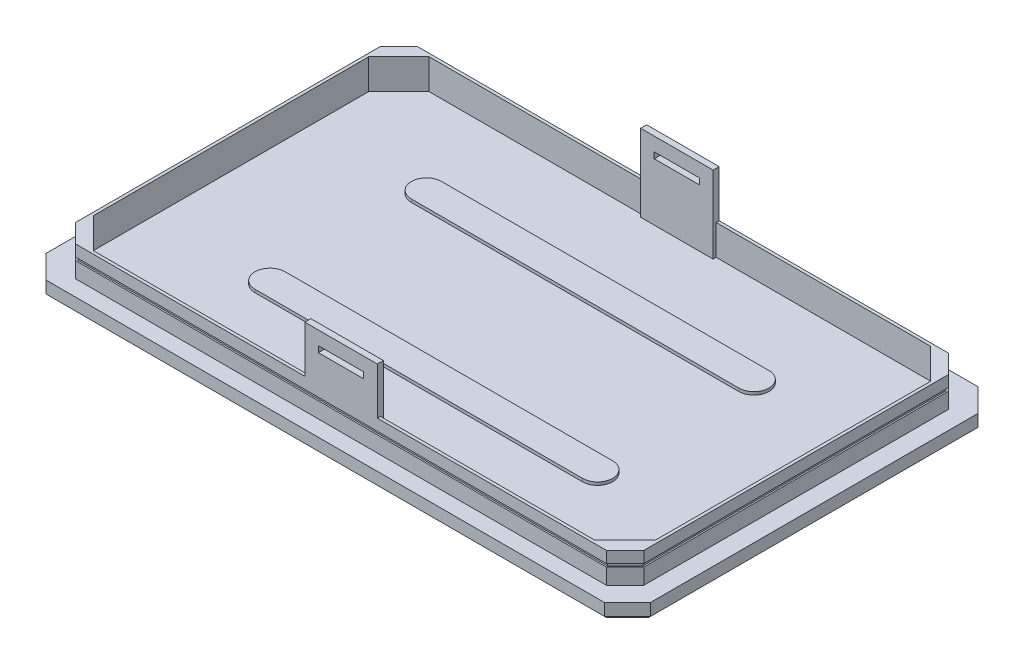
SolidWorks part; units mm, degrees
ref_plane "前视基准面" through (0, 0, 0) normal (0, 0, 1) x (1, 0, 0)
ref_plane "上视基准面" through (0, 0, 0) normal (0, 1, 0) x (1, 0, 0)
ref_plane "右视基准面" through (0, 0, 0) normal (1, 0, 0) x (0, 0, -1)
other "Configuration Table"
sketch "草图1" plane through (0, 0, 0) normal (0, 1, 0) x (1, 0, 0)
  line L0 (-100, 54.16) -> (-92.36, 61.8)
  line L1 (-92.36, -61.8) -> (92.36, -61.8)
  line L2 (-100, -54.16) -> (-100, 54.16)
  line L3 (-92.36, 61.8) -> (92.36, 61.8)
  line L4 (100, -54.16) -> (100, 54.16)
  line L5 (-100, -61.8) -> (100, 61.8) construction
  line L6 (-100, 61.8) -> (100, -61.8) construction
  line L7 (92.36, 61.8) -> (100, 54.16)
  line L8 (92.36, -61.8) -> (100, -54.16)
  line L9 (-100, -54.16) -> (-92.36, -61.8)
  point P0 (0, 0)
  dimension "D1" = 200
  dimension "D2" = 123.6
extrude "凸台-拉伸1" add sketch "草图1" along normal blind 5
sketch "草图2" plane through (0, 5, 0) normal (0, 1, 0) x (1, 0, 0)
  line L0 (-93.97, 50.37) -> (-87.79, 56.55)
  line L1 (-87.79, -56.55) -> (87.79, -56.55)
  line L2 (-93.97, -50.37) -> (-93.97, 50.37)
  line L3 (-87.79, 56.55) -> (87.79, 56.55)
  line L4 (93.97, -50.37) -> (93.97, 50.37)
  line L5 (-93.97, -56.55) -> (93.97, 56.55) construction
  line L6 (-93.97, 56.55) -> (93.97, -56.55) construction
  line L7 (-93.97, -50.37) -> (-87.79, -56.55)
  line L8 (87.79, -56.55) -> (93.97, -50.37)
  line L9 (87.79, 56.55) -> (93.97, 50.37)
  line L10 (-92.97, -45.55) -> (-82.97, -55.55)
  line L11 (-82.97, -55.55) -> (82.97, -55.55)
  line L12 (-92.97, -45.55) -> (-92.97, 45.55)
  line L13 (-82.97, 55.55) -> (82.97, 55.55)
  line L14 (92.97, -45.55) -> (92.97, 45.55)
  line L15 (-92.97, -55.55) -> (92.97, 55.55) construction
  line L16 (-92.97, 55.55) -> (92.97, -55.55) construction
  line L17 (-92.97, 45.55) -> (-82.97, 55.55)
  line L18 (92.97, 45.55) -> (82.97, 55.55)
  line L19 (82.97, -55.55) -> (92.97, -45.55)
  point P0 (0, 0)
  point P14 (0, 0)
  dimension "D1" = 113.1
  dimension "D2" = 187.94
  dimension "D3" = 1
  dimension "D4" = 1
extrude "凸台-拉伸2" add sketch "草图2" along normal blind 10
sketch "支撑架（待调整）" plane through (0, 0, 56.55) normal (0, 0, 1) x (1, 0, 0)
  line L6 (-68.0971, 44.5962) -> (-63.0971, 49.5962)
  line L7 (-49.2657, 49.5962) -> (-44.2657, 44.5962)
  line L9 (-68.0971, 25.3818) -> (-68.0971, 44.5962)
  line L10 (-63.0971, 49.5962) -> (-49.2657, 49.5962)
  line L11 (-44.2657, 22.3818) -> (-44.2657, 44.5962)
  line L12 (-44.2657, 22.3818) -> (-37.8806, 22.3818)
  line L13 (-74.4822, 22.3818) -> (-71.0971, 22.3818)
  line L17 (-80.8673, 15) -> (-74.4822, 22.3818)
  line L18 (-31.4955, 15) -> (-26.4471, 15)
  line L19 (-85.9157, 4.2346) -> (-26.4471, 4.2346)
  line L20 (-85.9157, 4.2346) -> (-85.9157, 15)
  line L21 (-85.9157, 15) -> (-80.8673, 15)
  line L22 (-26.4471, 4.2346) -> (-26.4471, 15)
  line L23 (-37.8806, 22.3818) -> (-31.4955, 15)
  line L24 (-71.0971, 22.3818) -> (-68.0971, 25.3818)
  line L25 (68.0971, 22.3818) -> (68.0971, 44.5962)
  line L27 (26.4471, 4.4781) -> (26.4471, 15)
  line L28 (44.2657, 25.3818) -> (44.2657, 44.5962)
  line L29 (31.4955, 15) -> (37.8806, 22.3818)
  line L30 (80.8673, 15) -> (85.9157, 15)
  line L31 (68.0971, 22.3818) -> (74.4822, 22.3818)
  line L32 (63.0971, 49.5962) -> (68.0971, 44.5962)
  line L33 (26.4471, 4.4781) -> (85.9157, 4.4781)
  line L34 (26.4471, 15) -> (31.4955, 15)
  line L35 (74.4822, 22.3818) -> (80.8673, 15)
  line L36 (49.2657, 49.5962) -> (63.0971, 49.5962)
  line L37 (37.8806, 22.3818) -> (41.2657, 22.3818)
  line L38 (44.2657, 44.5962) -> (49.2657, 49.5962)
  line L39 (85.9157, 4.4781) -> (85.9157, 15)
  line L40 (41.2657, 22.3818) -> (44.2657, 25.3818)
  point P0 (0, 15)
  point P9 (-56.1814, 15)
  point P10 (-56.1814, 15)
  point P11 (-44.2657, 49.5962)
  point P13 (-68.0971, 49.5962)
  point P15 (-68.0971, 22.3818)
  point P17 (-56.1814, 11.4723)
  point P27 (56.1814, 15)
  point P29 (56.1814, 15)
  point P30 (56.1814, 15)
  point P31 (68.0971, 49.5962)
  point P33 (44.2657, 49.5962)
  point P35 (44.2657, 22.3818)
  point P37 (56.1814, 11.4723)
sketch "草图6" plane through (72.17, 0, 72.17) normal (0.7071, 0, 0.7071) x (0.7071, 0, -0.7071)
  line L1 (21.4393, 10.6117) -> (31.2612, 10.6117)
  line L2 (21.4393, 10.6117) -> (21.4393, 10.2265)
  line L3 (21.4393, 10.2265) -> (31.2612, 10.2265)
  line L4 (31.2612, 10.6117) -> (31.2612, 10.2265)
  line L5 (21.4393, 10.6117) -> (31.2612, 10.2265) construction
  line L6 (21.4393, 10.2265) -> (31.2612, 10.6117) construction
  point P0 (26.3502, 10.4191)
extrude "切除-拉伸2" cut sketch "草图6" against normal blind 0.2
sketch "草图7" plane through (0, 5, 0) normal (0, 1, 0) x (1, 0, 0)
  line L5 (87.79, 56.55) -> (-87.79, 56.55) construction
  line L6 (-12, -56.55) -> (12, -56.55)
  line L12 (-12, -56.55) -> (-12, 56.55)
  line L13 (-12, 56.55) -> (12, 56.55)
  line L19 (12, -56.55) -> (12, 56.55)
  line L20 (-12, -56.55) -> (12, 56.55) construction
  line L22 (-12, 56.55) -> (12, -56.55) construction
  line L23 (93.97, -50.37) -> (93.97, 50.37) construction
  line L24 (-93.97, -12) -> (93.97, -12)
  line L25 (-93.97, -12) -> (-93.97, 12)
  line L26 (-93.97, 12) -> (93.97, 12)
  line L27 (93.97, -12) -> (93.97, 12)
  line L28 (-93.97, -12) -> (93.97, 12) construction
  line L29 (-93.97, 12) -> (93.97, -12) construction
  line L31 (-91.97, -54.55) -> (91.97, -54.55)
  line L32 (-91.97, -54.55) -> (-91.97, 54.55)
  line L33 (-91.97, 54.55) -> (91.97, 54.55)
  line L34 (91.97, -54.55) -> (91.97, 54.55)
  line L35 (-91.97, -54.55) -> (91.97, 54.55) construction
  line L36 (-91.97, 54.55) -> (91.97, -54.55) construction
  point P0 (0, 0)
  point P8 (0, 0)
  point P15 (0, 0)
  line M14 (-82.97, -55.55) -> (82.97, -55.55)
  line M18 (82.97, 55.55) -> (-82.97, 55.55)
  dimension "D1" = 24
  dimension "D2" = 24
  dimension "D3" = 2
  dimension "D4" = 2
extrude "凸台-拉伸6" add sketch "草图7" along normal blind 25.5 contours L12 L33 L19 M18 | L19 L13 L12 M18 | L31 L12 L19 M14 | L6 L19 L12 M14
sketch "草图5" plane through (0, 10.2265, 0) normal (0, 1, 0) x (1, 0, 0)
  line L0 (-87.79, -56.55) -> (87.79, -56.55)
  line L1 (87.79, -56.55) -> (93.97, -50.37)
  line L2 (93.97, -50.37) -> (93.97, 50.37)
  line L3 (93.97, 50.37) -> (87.79, 56.55)
  line L4 (87.79, 56.55) -> (-87.79, 56.55)
  line L5 (-87.79, 56.55) -> (-93.97, 50.37)
  line L6 (-93.97, 50.37) -> (-93.97, -50.37)
  line L7 (-93.97, -50.37) -> (-87.79, -56.55)
  line L8 (87.5829, 56.05) -> (93.47, 50.1629)
  line L9 (-87.5829, -56.05) -> (87.5829, -56.05)
  line L10 (-93.47, -50.1629) -> (-93.47, 50.1629)
  line L11 (-87.5829, 56.05) -> (87.5829, 56.05)
  line L12 (93.47, -50.1629) -> (93.47, 50.1629)
  line L13 (87.5829, -56.05) -> (93.47, -50.1629)
  line L14 (-93.47, -50.1629) -> (-87.5829, -56.05)
  line L15 (-87.5829, 56.05) -> (-93.47, 50.1629)
  point P4 (0, 0)
  dimension "D1" = 0.5
  dimension "D2" = 0.5
  dimension "D3" = 0.5
extrude "切除-拉伸3" cut sketch "草图5" along normal blind 1
sketch "草图13" plane through (0, 0, 56.55) normal (0, 0, 1) x (1, 0, 0)
  line L1 (0, 24) -> (7.5, 24)
  line L2 (0, 24) -> (-7.5, 24)
  line L3 (7.5, 24) -> (7.5, 26)
  line L4 (7.5, 26) -> (-7.5, 26)
  line L5 (-7.5, 26) -> (-7.5, 24)
extrude "切除-拉伸6" cut sketch "草图13" against normal blind 117.5
sketch "草图17" plane through (0, 5, 0) normal (0, 1, 0) x (1, 0, 0)
  line L0 (-54.17, -25.8642) -> (54.17, -25.8642) construction
  line L2 (-54.17, -25.8642) -> (54.17, -25.8642)
  line L3 (-54.17, -20.8642) -> (54.17, -20.8642)
  line L4 (-54.17, -30.8642) -> (54.17, -30.8642)
  line L5 (-93.97, 0) -> (93.97, 0)
  line L6 (-93.97, 50.37) -> (-93.97, -50.37) construction
  line L7 (93.97, -50.37) -> (93.97, 50.37) construction
  line L8 (-54.17, 25.8642) -> (54.17, 25.8642) construction
  line L9 (-54.17, 20.8642) -> (54.17, 20.8642)
  line L10 (-54.17, 30.8642) -> (54.17, 30.8642)
  arc A2 (-54.17, -20.8642) -> (-54.17, -30.8642) centre (-54.17, -25.8642) ccw
  arc A3 (54.17, -30.8642) -> (54.17, -20.8642) centre (54.17, -25.8642) ccw
  arc A4 (-54.17, 20.8642) -> (-54.17, 30.8642) centre (-54.17, 25.8642) cw
  arc A5 (54.17, 30.8642) -> (54.17, 20.8642) centre (54.17, 25.8642) cw
  point P0 (0, -25.8642)
  point P15 (0, 25.8642)
extrude "凸台-拉伸7" add sketch "草图17" along normal blind 1
sketch "草图18" plane through (0, 6, 0) normal (0, 1, 0) x (1, 0, 0)
  line L0 (-54.17, 30.8642) -> (54.17, 30.8642) construction
  line L1 (-1.6402, -30.8642) -> (1.6402, -30.8642)
  line L2 (-1.6402, -30.8642) -> (-1.6402, 30.8642)
  line L3 (-1.6402, 30.8642) -> (1.6402, 30.8642)
  line L4 (1.6402, -30.8642) -> (1.6402, 30.8642)
  line L5 (-1.6402, -30.8642) -> (1.6402, 30.8642) construction
  line L6 (-1.6402, 30.8642) -> (1.6402, -30.8642) construction
  point P0 (0, 0)
chamfer "倒角3" distance 1 angle 45 8 edges at (-96.18, 0, 57.98) (0, 0, 61.8) (96.18, 0, 57.98) (100, 0, 0) (96.18, 0, -57.98) (0, 0, -61.8) (-96.18, 0, -57.98) (-100, 0, 0)
